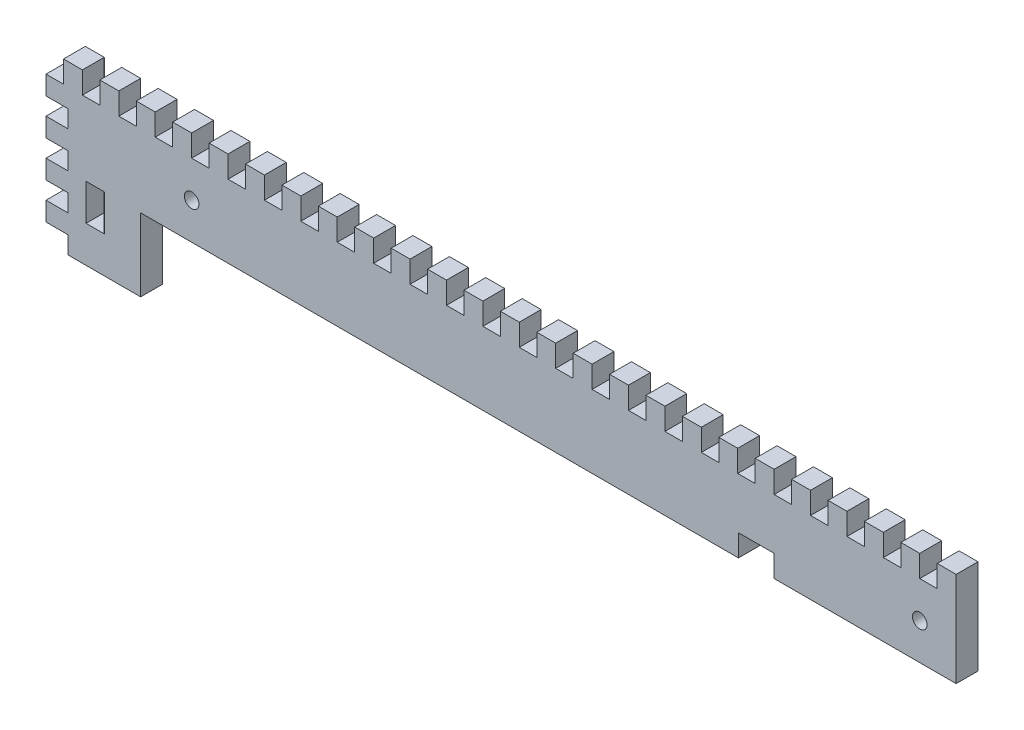
SolidWorks part; units mm, degrees
ref_plane "Plan de face" through (0, 0, 0) normal (0, 0, 1) x (1, 0, 0)
ref_plane "Plan de dessus" through (0, 0, 0) normal (0, 1, 0) x (1, 0, 0)
ref_plane "Plan de droite" through (0, 0, 0) normal (1, 0, 0) x (0, 0, -1)
sketch "Esquisse1" plane through (0, 0, 0) normal (0, 0, 1) x (1, 0, 0)
  line L0 (0, 0) -> (0, 26)
  line L1 (0, 26) -> (-5.2, 26)
  line L2 (-5.2, 26) -> (-5.2, 20)
  line L3 (-5.2, 20) -> (-10, 20)
  line L4 (-10, 20) -> (-10, 26)
  line L5 (0, 0) -> (-50, 0) construction
  line L6 (-10, 26) -> (-15.2, 26)
  line L7 (-15.2, 26) -> (-15.2, 20)
  line L8 (-15.2, 20) -> (-20, 20)
  line L9 (-20, 20) -> (-20, 26)
  line L10 (-20, 26) -> (-25.2, 26)
  line L11 (-25.2, 26) -> (-25.2, 20)
  line L12 (-25.2, 20) -> (-30, 20)
  line L13 (-30, 20) -> (-30, 26)
  line L14 (-30, 26) -> (-35.2, 26)
  line L15 (-35.2, 26) -> (-35.2, 20)
  line L16 (-35.2, 20) -> (-40, 20)
  line L17 (-40, 20) -> (-40, 26)
  line L18 (-40, 26) -> (-45.2, 26)
  line L19 (-45.2, 26) -> (-45.2, 20)
  line L20 (-45.2, 20) -> (-50, 20)
  line L21 (-50, 20) -> (-50, 26)
  line L22 (-50, 26) -> (-55.2, 26)
  line L23 (-55.2, 26) -> (-55.2, 20)
  line L24 (-55.2, 20) -> (-60, 20)
  line L25 (-60, 20) -> (-60, 26)
  line L26 (-60, 26) -> (-65.2, 26)
  line L27 (-65.2, 26) -> (-65.2, 20)
  line L28 (-65.2, 20) -> (-70, 20)
  line L29 (-70, 20) -> (-70, 26)
  line L30 (-70, 26) -> (-75.2, 26)
  line L31 (-75.2, 26) -> (-75.2, 20)
  line L32 (-75.2, 20) -> (-80, 20)
  line L33 (-80, 20) -> (-80, 26)
  line L34 (-80, 26) -> (-85.2, 26)
  line L35 (-85.2, 26) -> (-85.2, 20)
  line L36 (-85.2, 20) -> (-90, 20)
  line L37 (-90, 20) -> (-90, 26)
  line L38 (-90, 26) -> (-95.2, 26)
  line L39 (-95.2, 26) -> (-95.2, 20)
  line L40 (-95.2, 20) -> (-100, 20)
  line L41 (-100, 20) -> (-100, 26)
  line L42 (-100, 26) -> (-105.2, 26)
  line L43 (-105.2, 26) -> (-105.2, 20)
  line L44 (-105.2, 20) -> (-110, 20)
  line L45 (-110, 20) -> (-110, 26)
  line L46 (-110, 26) -> (-115.2, 26)
  line L47 (-115.2, 26) -> (-115.2, 20)
  line L48 (-115.2, 20) -> (-120, 20)
  line L49 (-120, 20) -> (-120, 26)
  line L50 (-120, 26) -> (-125.2, 26)
  line L51 (-125.2, 26) -> (-125.2, 20)
  line L52 (-125.2, 20) -> (-130, 20)
  line L53 (-130, 20) -> (-130, 26)
  line L54 (-130, 26) -> (-135.2, 26)
  line L55 (-135.2, 26) -> (-135.2, 20)
  line L56 (-135.2, 20) -> (-140, 20)
  line L57 (-140, 20) -> (-140, 26)
  line L58 (-140, 26) -> (-145.2, 26)
  line L59 (-145.2, 26) -> (-145.2, 20)
  line L60 (-145.2, 20) -> (-150, 20)
  line L61 (-150, 20) -> (-150, 26)
  line L62 (-150, 26) -> (-155.2, 26)
  line L63 (-155.2, 26) -> (-155.2, 20)
  line L64 (-155.2, 20) -> (-160, 20)
  line L65 (-160, 20) -> (-160, 26)
  line L66 (-160, 26) -> (-165.2, 26)
  line L67 (-165.2, 26) -> (-165.2, 20)
  line L68 (-165.2, 20) -> (-170, 20)
  line L69 (-170, 20) -> (-170, 26)
  line L70 (-170, 26) -> (-175.2, 26)
  line L71 (-175.2, 26) -> (-175.2, 20)
  line L72 (-175.2, 20) -> (-180, 20)
  line L73 (-180, 20) -> (-180, 26)
  line L74 (-180, 26) -> (-185.2, 26)
  line L75 (-185.2, 26) -> (-185.2, 20)
  line L76 (-185.2, 20) -> (-190, 20)
  line L77 (-190, 20) -> (-190, 26)
  line L78 (-190, 26) -> (-195.2, 26)
  line L79 (-195.2, 26) -> (-195.2, 20)
  line L80 (-195.2, 20) -> (-200, 20)
  line L81 (-200, 20) -> (-200, 26)
  line L82 (-200, 26) -> (-205.2, 26)
  line L83 (-205.2, 26) -> (-205.2, 20)
  line L84 (-205.2, 20) -> (-210, 20)
  line L85 (-210, 20) -> (-210, 26)
  line L86 (-210, 26) -> (-215.2, 26)
  line L87 (-215.2, 26) -> (-215.2, 20)
  line L88 (-215.2, 20) -> (-220, 20)
  line L89 (-220, 20) -> (-220, 26)
  line L90 (-220, 26) -> (-225.2, 26)
  line L91 (-225.2, 26) -> (-225.2, 20)
  line L92 (-225.2, 20) -> (-230, 20)
  line L93 (-230, 20) -> (-230, 26)
  line L94 (-230, 26) -> (-235.2, 26)
  line L95 (-235.2, 26) -> (-235.2, 20)
  line L96 (-235.2, 20) -> (-240, 20)
  line L97 (-240, 20) -> (-240, 26)
  line L98 (-240, 26) -> (-245.2, 26)
  line L99 (-245.2, 26) -> (-245.2, 20)
  line L100 (-245.2, 20) -> (-250, 20)
  line L101 (-250, 20) -> (-250, 14.8)
  line L102 (-250, 20) -> (-250, 26) [skipped]
  line L103 (-250, 14.8) -> (-244, 14.8)
  line L104 (-244, 14.8) -> (-244, 10)
  line L105 (-244, 10) -> (-250, 10)
  line L106 (-250, 10) -> (-250, 4.8)
  line L107 (-250, 4.8) -> (-244, 4.8)
  line L108 (-244, 4.8) -> (-244, 0)
  line L109 (-244, 0) -> (-250, 0)
  line L110 (-250, 0) -> (-250, -5.2)
  line L111 (-250, -5.2) -> (-244, -5.2)
  line L112 (-244, -5.2) -> (-244, -10)
  line L113 (-244, -10) -> (-250, -10)
  line L114 (-250, -10) -> (-250, -15.2)
  line L115 (-250, -15.2) -> (-244, -15.2)
  line L116 (-244, -15.2) -> (-244, -20)
  line L117 (-244, -20) -> (-224, -20)
  line L118 (-244, -20) -> (-250, -20) [skipped]
  line L119 (-224, -20) -> (-224, 0)
  line L120 (-224, 0) -> (-59.8, 0)
  line L121 (-59.8, 0) -> (-59.8, 6)
  line L122 (-239, 0) -> (-234, 0)
  line L123 (-239, 0) -> (-239, -10)
  line L124 (-239, -10) -> (-234, -10)
  line L125 (-234, 0) -> (-234, -10)
  line L126 (-59.8, 6) -> (-50, 6)
  line L127 (-50, 6) -> (-50, 0)
  line L128 (-50, 0) -> (0, 0)
  line L129 (-59.8, 0) -> (-277.7246, 0) construction
  circle A0 centre (-210, 10) radius 2
  circle A1 centre (-10, 10) radius 2
  dimension "D11" = 4
  dimension "D12" = 4
  dimension "D13" = 200
  dimension "D14" = 10
  dimension "D15" = 10
  dimension "D1" = 26
  dimension "D2" = 5.2
  dimension "D3" = 4.8
  dimension "D4" = 6
  dimension "D5" = 6
  dimension "D7" = 20
  dimension "D8" = 4.8
  dimension "D9" = 5.2
  dimension "D16" = 5
  dimension "D17" = 10
  dimension "D18" = 10
  dimension "D19" = 5
  dimension "D20" = 6
  dimension "D21" = 9.8
  dimension "D22" = 50
  dimension "D6" = 25
  dimension "D10" = 4
extrude "Boss.-Extru.1" add sketch "Esquisse1" along normal blind 6
